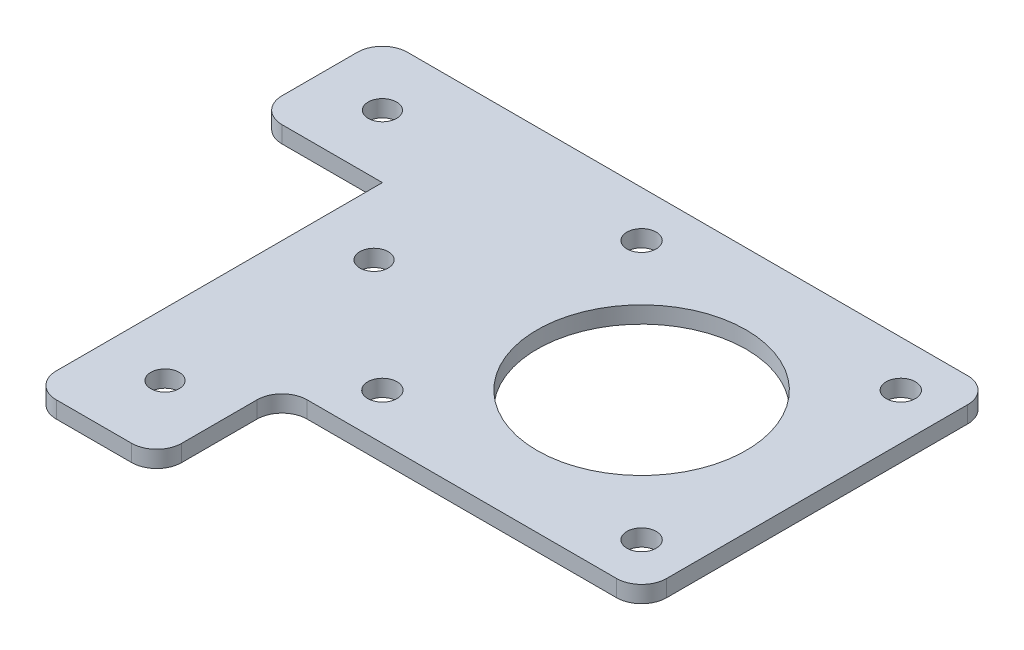
SolidWorks part; units mm, degrees
ref_plane "前视基准面" through (0, 0, 0) normal (0, 0, 1) x (1, 0, 0)
ref_plane "上视基准面" through (0, 0, 0) normal (0, 1, 0) x (1, 0, 0)
ref_plane "右视基准面" through (0, 0, 0) normal (1, 0, 0) x (0, 0, -1)
other "Configuration Table"
sketch "草图1" plane through (0, 0, 0) normal (0, 1, 0) x (1, 0, 0)
  line L0 (0, 0) -> (-12, 0)
  line L1 (0, 0) -> (0, -32.8247)
  line L2 (15, 0) -> (15, -27) construction
  line L3 (15, 15) -> (-12, 15)
  line L4 (15, 15) -> (55, 15)
  line L5 (58, 12) -> (58, -24)
  line L6 (55, -27) -> (18, -27)
  line L7 (22.7253, -6) -> (51.5605, -6) construction
  line L8 (37, 9.4736) -> (37, -18.1798) construction
  line L9 (7.5, 0) -> (7.5, -53.5236) construction
  line L10 (0, 0) -> (0, 15) construction
  line L11 (0, 0) -> (15, 0) construction
  line L12 (0, 7.5) -> (-46.0436, 7.5) construction
  line L14 (-15, 12) -> (-15, 3)
  line L15 (15, -30) -> (15, -39)
  line L16 (12, -42) -> (3, -42)
  line L17 (0, -39) -> (0, -32.8247)
  line L18 (-28.0085, -21) -> (26.9909, -21) construction
  circle A0 centre (37, -6) radius 12.5
  circle A1 centre (52.5, -21.5) radius 1.75
  circle A2 centre (21.5, -21.5) radius 1.75
  circle A3 centre (21.5, 9.5) radius 1.75
  circle A4 centre (52.5, 9.5) radius 1.75
  arc A5 (55, -27) -> (58, -24) centre (55, -24) ccw
  arc A6 (58, 12) -> (55, 15) centre (55, 12) ccw
  circle A7 centre (7.5, -8.5) radius 1.7
  circle A8 centre (7.5, -33.5) radius 1.7
  arc A9 (-12, 0) -> (-15, 3) centre (-12, 3) cw
  arc A10 (-15, 12) -> (-12, 15) centre (-12, 12) cw
  arc A11 (18, -27) -> (15, -30) centre (18, -30) ccw
  arc A12 (0, -39) -> (3, -42) centre (3, -39) ccw
  arc A13 (12, -42) -> (15, -39) centre (12, -39) ccw
  circle A15 centre (-7.5, 7.5) radius 1.7
  point P28 (58, -27)
  point P31 (58, 15)
  point P54 (0, -42)
  point P57 (15, -42)
  dimension "D6" = 25
  dimension "D7" = 3.5
  dimension "D8" = 31
  dimension "D10" = 3
  dimension "D11" = 3.4
  dimension "D14" = 3
  dimension "D16" = 3.4
  dimension "D18" = 7.5
  dimension "D2" = 15
  dimension "D3" = 42
  dimension "D4" = 58
  dimension "D5" = 21
  dimension "D9" = 31
  dimension "D12" = 15
  dimension "D13" = 15
  dimension "D15" = 25
  dimension "D17" = 15
extrude "凸台-拉伸2" add sketch "草图1" along normal blind 2
